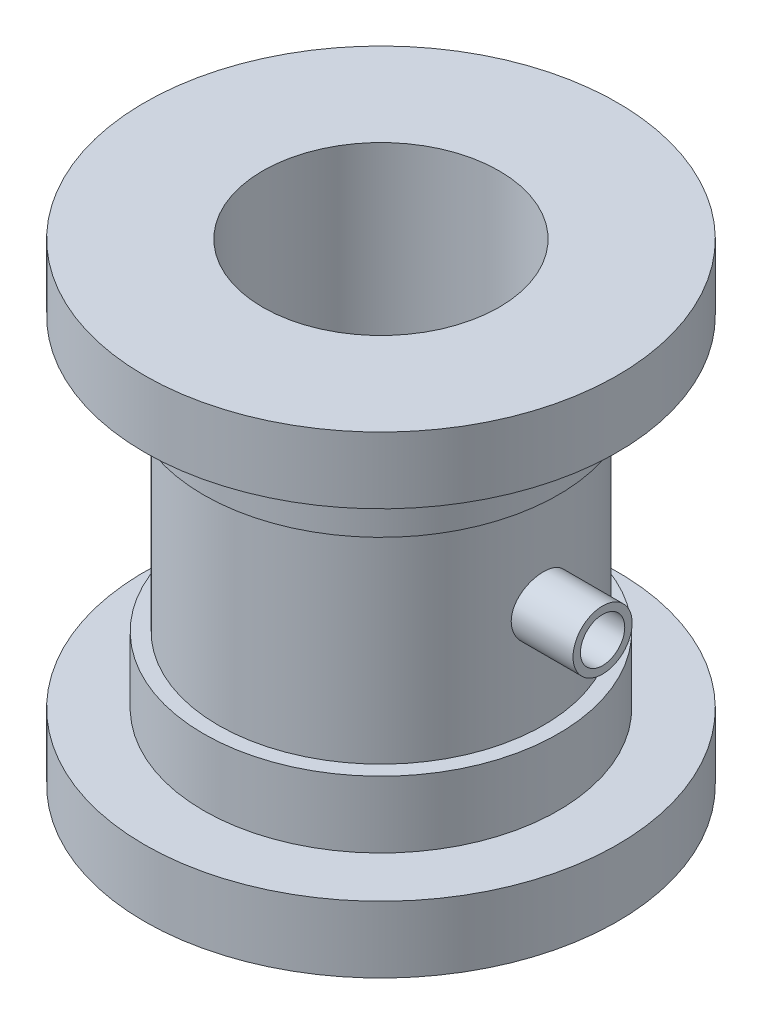
SolidWorks part; units mm, degrees
ref_plane "Front Plane" through (0, 0, 0) normal (0, 0, 1) x (1, 0, 0)
ref_plane "Top Plane" through (0, 0, 0) normal (0, 1, 0) x (1, 0, 0)
ref_plane "Right Plane" through (0, 0, 0) normal (1, 0, 0) x (0, 0, -1)
sketch "Sketch1" plane through (0, 0, 0) normal (0, 1, 0) x (1, 0, 0)
  circle A0 centre (0, 0) radius 24
  circle A1 centre (0, 0) radius 22
  circle A2 centre (0, 0) radius 32
  dimension "D1" = 48
  dimension "D2" = 44
  dimension "D3" = 64
extrude "Boss-Extrude1" add sketch "Sketch1" along normal blind 28 contours A1
sketch "Sketch2" plane through (0, 28, 0) normal (0, 1, 0) x (1, 0, 0)
  circle A0 centre (0, 0) radius 24
  dimension "D1" = 48
extrude "Boss-Extrude5" add sketch "Sketch2" along normal blind 9
sketch "Sketch3" plane through (0, 37, 0) normal (0, 1, 0) x (1, 0, 0)
  circle A0 centre (0, 0) radius 32
  dimension "D1" = 64
extrude "Boss-Extrude6" add sketch "Sketch3" along normal blind 9
ref_plane "Plane1" through (0, 14, 0) normal (0, -1, 0) x (-1, 0, 0)
mirror "Mirror1" about plane through (0, 14, 0) normal (0, -1, 0) of bodies 106
hole_wizard "Ø8.0mm Dowel Hole1" positions "Sketch4" profile "Sketch5" hole size "Ø8.0" standard "ANSI Metric" end condition through all
sketch "Sketch4" plane through (0, -18, 0) normal (0, -1, 0) x (-1, 0, 0)
  point P0 (0, 0)
sketch "Sketch5" plane through (0, -18, 0) normal (1, 0, 0) x (0, 0, -1)
  line L0 (0, 0) -> (0, 64)
  line L1 (0, 64) -> (16, 64)
  line L2 (16, 64) -> (16, 0)
  line L5 (16, 0) -> (0, 0)
  line L11 (0, -6.35) -> (0, 107.95) construction
  dimension "Thru Hole Dia." = 32
  dimension "Thru Hole Depth" = 64
sketch "Sketch7" plane through (0, 0, 0) normal (1, 0, 0) x (0, 0, -1)
  line L0 (0, -18) -> (0, 46)
  line L1 (16, 46) -> (-16, 46) construction
  line L2 (-16, -18) -> (16, -18) construction
  circle A0 centre (0, 14) radius 4
  dimension "D1" = 8
extrude "Boss-Extrude8" add sketch "Sketch7" along normal blind 30 contours L0 A0 | L0 A0
sketch "Sketch8" plane through (0, -18, 0) normal (0, -1, 0) x (1, 0, 0)
  line L0 (14.3793, 7.0167) -> (-2.2995, 7.0167)
  line L1 (-2.2995, 7.0167) -> (-2.2995, -6.7363)
  line L2 (-2.2995, -6.7363) -> (14.5128, -6.7363)
  arc A0 (14.3793, 7.0167) -> (14.5128, -6.7363) centre (0, 0) cw
  circle A1 centre (0, 0) radius 16 construction
extrude "Cut-Extrude1" cut sketch "Sketch8" against normal through all
sketch "Sketch9" plane through (30, 0, 0) normal (1, 0, 0) x (0, 0, -1)
  circle A0 centre (0, 14) radius 3
  dimension "D1" = 6
extrude "Cut-Extrude2" cut sketch "Sketch9" against normal through all
